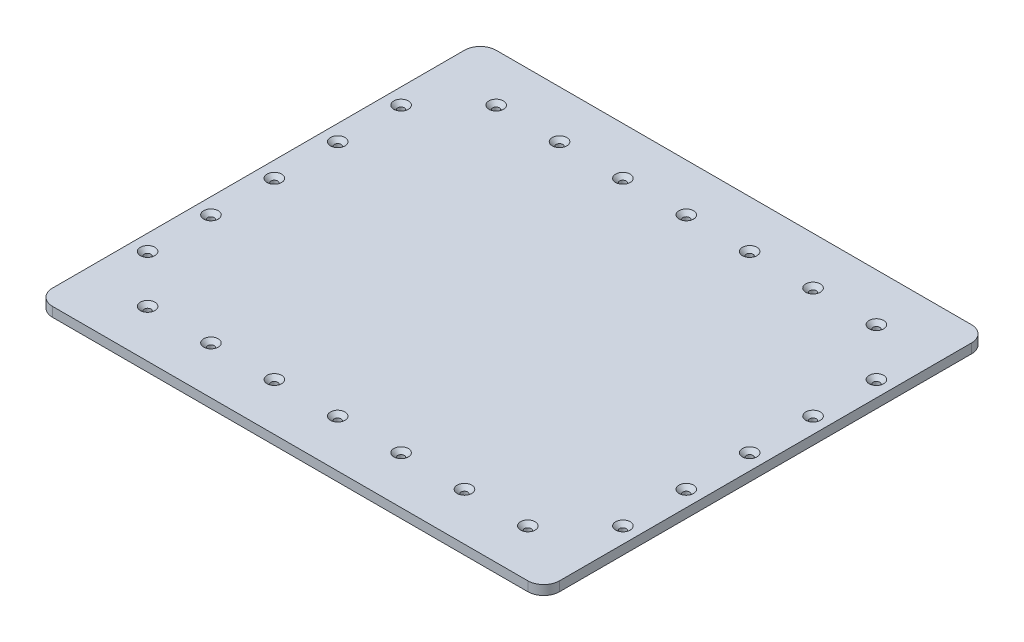
SolidWorks part; units mm, degrees
ref_plane "前视基准面" through (0, 0, 0) normal (0, 0, 1) x (1, 0, 0)
ref_plane "上视基准面" through (0, 0, 0) normal (0, 1, 0) x (1, 0, 0)
ref_plane "右视基准面" through (0, 0, 0) normal (1, 0, 0) x (0, 0, -1)
other "Configuration Table"
sketch "草图1" plane through (0, 0, 0) normal (0, 1, 0) x (1, 0, 0)
  line L1 (-150, -140) -> (150, -140)
  line L2 (-160, -130) -> (-160, 130)
  line L3 (-150, 140) -> (150, 140)
  line L4 (160, -130) -> (160, 130)
  line L5 (-160, -140) -> (-156.8729, -137.2638) construction
  line L6 (-160, 140) -> (-156.8729, 137.2638) construction
  line L8 (156.8729, 137.2638) -> (160, 140) construction
  line L9 (156.8729, -137.2638) -> (160, -140) construction
  arc A0 (150, -140) -> (160, -130) centre (150, -130) ccw
  arc A1 (-160, 130) -> (-150, 140) centre (-150, 130) cw
  arc A2 (-150, -140) -> (-160, -130) centre (-150, -130) cw
  arc A3 (150, 140) -> (160, 130) centre (150, 130) cw
  point P0 (0, 0)
  dimension "D3" = 10
  dimension "D1" = 320
  dimension "D2" = 280
extrude "凸台-拉伸1" add sketch "草图1" along normal mid plane 6
sketch "草图5" plane through (0, 3, 0) normal (0, 1, 0) x (1, 0, 0)
  line L0 (0, 0) -> (0, 142.7283) construction
  line L1 (160, 0) -> (-160, 0) construction
  line L2 (-160, 130) -> (-160, -130) construction
  line L3 (150, 140) -> (-150, 140) construction
  circle A0 centre (0, 110) radius 2.1
  circle A16 centre (40, 110) radius 2.1
  circle A17 centre (80, 110) radius 2.1
  circle A18 centre (120, 110) radius 2.1
  circle A19 centre (-120, 110) radius 2.1
  circle A20 centre (-80, 110) radius 2.1
  circle A21 centre (-40, 110) radius 2.1
  circle A22 centre (-40, -110) radius 2.1
  circle A23 centre (-80, -110) radius 2.1
  circle A24 centre (-120, -110) radius 2.1
  circle A25 centre (120, -110) radius 2.1
  circle A26 centre (80, -110) radius 2.1
  circle A27 centre (40, -110) radius 2.1
  circle A28 centre (0, -110) radius 2.1
  circle A29 centre (-150, 0) radius 2.1
  circle A30 centre (-150, -40) radius 2.1
  circle A31 centre (-150, -80) radius 2.1
  circle A32 centre (-150, 80) radius 2.1
  circle A33 centre (-150, 40) radius 2.1
  circle A34 centre (150, 40) radius 2.1
  circle A35 centre (150, 80) radius 2.1
  circle A36 centre (150, -80) radius 2.1
  circle A37 centre (150, -40) radius 2.1
  circle A38 centre (150, 0) radius 2.1
  dimension "D2" = 4.2
  dimension "D1" = 4.2
  dimension "D3" = 10
  dimension "D4" = 30
extrude "切除-拉伸4" cut sketch "草图5" against normal blind 240
chamfer "倒角2" distance 2.5 angle 45 24 edges at (150, 3, 37.9) (150, 3, 77.9) (120, 3, 107.9) (80, 3, 107.9) (40, 3, 107.9) (0, 3, 107.9) (-40, 3, 112.1) (-80, 3, 112.1) (-120, 3, 112.1) (-150, 3, 82.1) (-150, 3, 42.1) (-150, 3, 2.1) (-150, 3, -42.1) (-150, 3, -82.1) (-120, 3, -112.1) (-80, 3, -112.1) (-40, 3, -112.1) (0, 3, -107.9) (40, 3, -107.9) (150, 3, -2.1) (150, 3, -37.9) (80, 3, -107.9) (120, 3, -107.9) (150, 3, -77.9)
